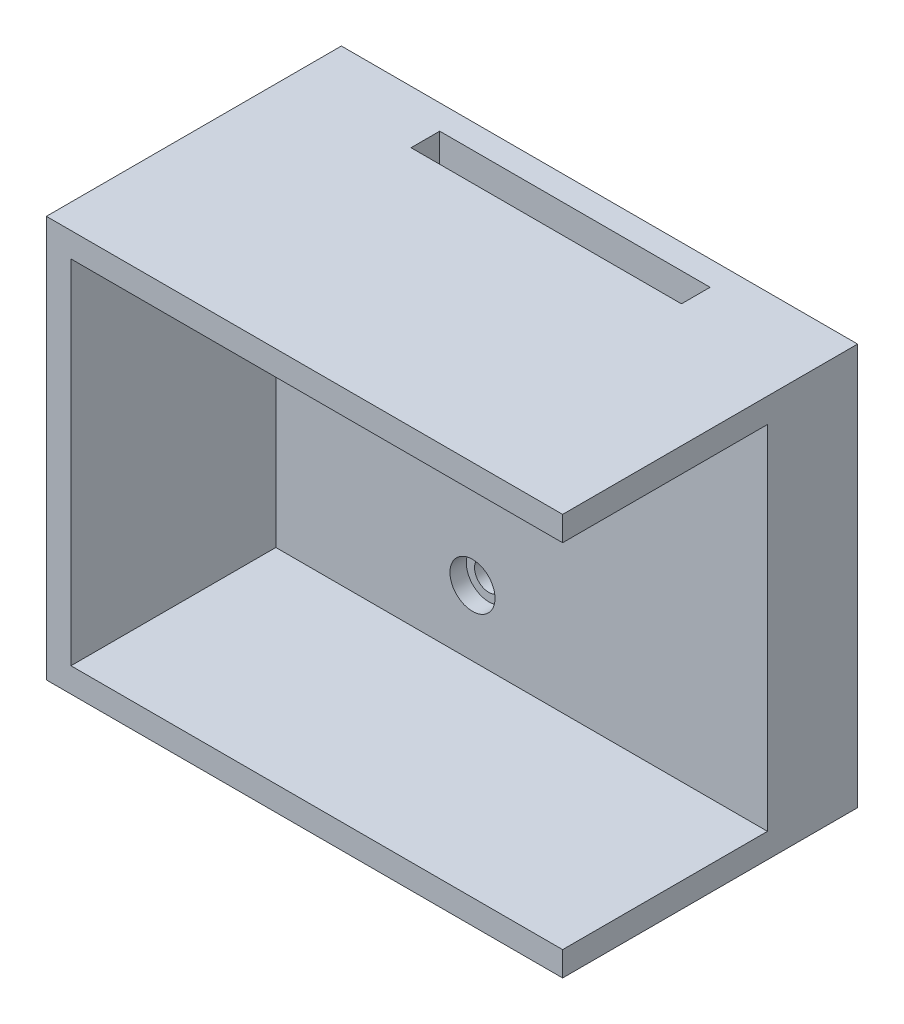
SolidWorks part; units mm, degrees
ref_plane "前视基准面" through (0, 0, 0) normal (0, 0, 1) x (1, 0, 0)
ref_plane "上视基准面" through (0, 0, 0) normal (0, 1, 0) x (1, 0, 0)
ref_plane "右视基准面" through (0, 0, 0) normal (1, 0, 0) x (0, 0, -1)
other "Configuration Table"
sketch "草图1" plane through (0, 0, 0) normal (0, 0, 1) x (1, 0, 0)
  line L0 (0, 43) -> (0, 46)
  line L1 (0, 0) -> (-50, 0)
  line L3 (0, 43) -> (-50, 43)
  line L4 (-50, 0) -> (-50, 43)
  line L5 (0, 46) -> (-53, 46)
  line L6 (-53, 46) -> (-53, -3)
  line L7 (-53, -3) -> (0, -3)
  line L8 (0, -3) -> (0, 0)
  dimension "D1" = 43
  dimension "D2" = 50
  dimension "D3" = 53
  dimension "D4" = 3
  dimension "D5" = 3
extrude "凸台-拉伸1" add sketch "草图1" along normal blind 25
sketch "草图2" plane through (0, 0, 0) normal (0, 0, -1) x (-1, 0, 0)
  line L1 (0, 46) -> (53, 46)
  line L2 (0, 46) -> (0, -3)
  line L3 (0, -3) -> (53, -3)
  line L4 (53, 46) -> (53, -3)
extrude "凸台-拉伸2" add sketch "草图2" along normal blind 11
sketch "草图4" plane through (0, 0, 0) normal (0, 0, 1) x (1, 0, 0)
  line L0 (0, 43) -> (0, 0) construction
  line L1 (-50, 43) -> (0, 43) construction
  line L3 (0, 0) -> (-50, 0) construction
  circle A0 centre (-26, 35) radius 2.75
  circle A1 centre (-26, 8) radius 2.75
  dimension "D1" = 5.5
  dimension "D6" = 5.5
  dimension "D2" = 26
  dimension "D3" = 8
  dimension "D4" = 26
  dimension "D5" = 8
extrude "切除-拉伸1" cut sketch "草图4" against normal blind 2
sketch "草图5" plane through (0, 0, -2) normal (0, 0, 1) x (1, 0, 0)
  circle A0 centre (-26, 8) radius 1.75
  circle A1 centre (-26, 35) radius 1.75
  dimension "D1" = 3.5
  dimension "D2" = 3.5
extrude "切除-拉伸2" cut sketch "草图5" against normal through all
sketch "草图8" plane through (0, -3, 0) normal (0, -1, 0) x (1, 0, 0)
  line L0 (0, 25) -> (0, -11) construction
  line L1 (-38, -4.5) -> (-5, -4.5)
  line L2 (-38, -4.5) -> (-38, -8)
  line L3 (-38, -8) -> (-5, -8)
  line L4 (-5, -4.5) -> (-5, -8)
  line L5 (-53, 25) -> (-53, -11) construction
  line L6 (0, -11) -> (-53, -11) construction
  dimension "D1" = 5
  dimension "D2" = 15
  dimension "D3" = 3
  dimension "D4" = 3.5
extrude "切除-拉伸3" cut sketch "草图8" against normal through all
sketch "草图9" plane through (0, 0, 0) normal (1, 0, 0) x (0, 0, -1)
  line L8 (-25, 43) -> (0, 43)
  line L9 (0, 43) -> (0, 0)
  line L10 (0, 0) -> (-25, 0)
  line L11 (-25, 0) -> (-25, -3)
  line L12 (-25, -3) -> (11, -3)
  line L13 (11, -3) -> (11, 46)
  line L14 (11, 46) -> (-25, 46)
  line L15 (-25, 46) -> (-25, 43)
  line L16 (-25, 43) -> (0, 43)
  line L17 (0, 43) -> (0, 0)
  line L18 (0, 0) -> (-25, 0)
  line L19 (-25, 0) -> (-25, -3)
  line L20 (-25, -3) -> (11, -3)
  line L21 (11, -3) -> (11, 46)
  line L22 (11, 46) -> (-25, 46)
  line L23 (-25, 46) -> (-25, 43)
  dimension "D1" = 0
extrude "凸台-拉伸3" add sketch "草图9" along normal blind 10
